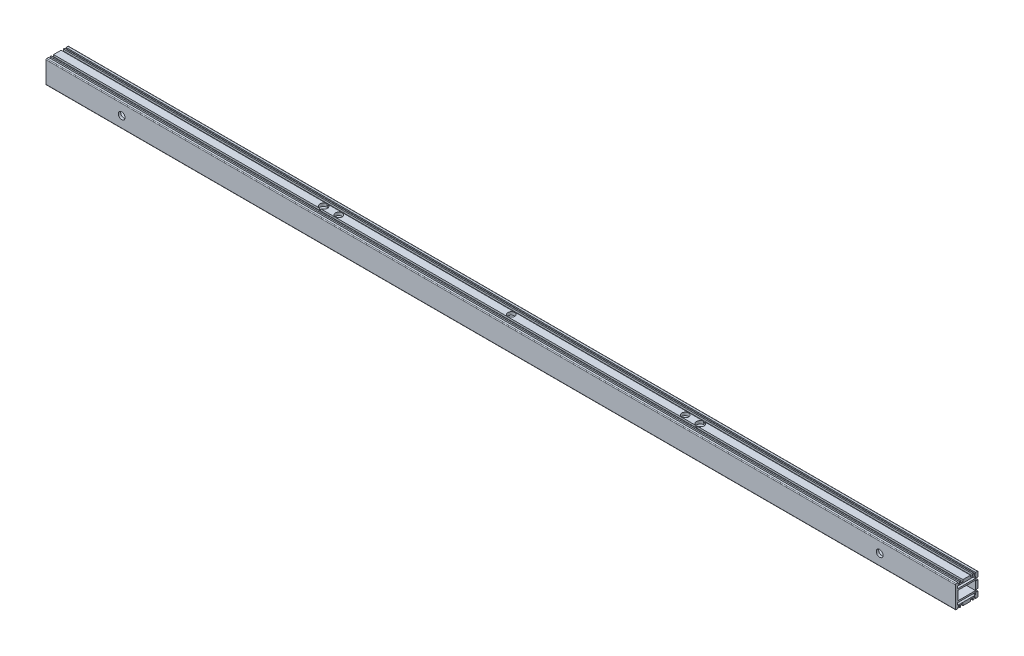
SolidWorks part; units mm, degrees
ref_plane "前视基准面" through (0, 0, 0) normal (0, 0, 1) x (1, 0, 0)
ref_plane "上视基准面" through (0, 0, 0) normal (0, 1, 0) x (1, 0, 0)
ref_plane "右视基准面" through (0, 0, 0) normal (1, 0, 0) x (0, 0, -1)
sketch "草图1" plane through (0, 0, 0) normal (1, 0, 0) x (0, 0, -1)
  line L0 (-15, 15) -> (15, -15) construction
  line L1 (-14, 15) -> (-11.5, 15)
  line L2 (-15, 14) -> (-15, -14)
  line L3 (-14, -15) -> (-11.5, -15)
  line L4 (15, 14) -> (15, 8)
  line L5 (15, 15) -> (-15, -15) construction
  line L6 (-11.5, 15) -> (-11.5, 13.5)
  line L7 (-11.5, 13.5) -> (-11.4, 13.5)
  line L8 (-11, 13.1) -> (-11, 12)
  line L9 (-11, 12) -> (-9.5, 12)
  line L10 (-9.5, 12) -> (-9.5, 15)
  line L11 (-9.5, 15) -> (-8, 15)
  line L12 (-8, 15) -> (-8, 12.5)
  line L13 (-8, 12.5) -> (-5, 12.5)
  line L14 (-5, 12.5) -> (-5, 15)
  line L15 (-5, 15) -> (5, 15)
  line L16 (0, 21.5201) -> (0, -18.309) construction
  line L17 (0, 55) -> (0, -55) construction
  line L18 (5, 12.5) -> (5, 15)
  line L19 (8, 12.5) -> (5, 12.5)
  line L20 (8, 15) -> (8, 12.5)
  line L21 (9.5, 15) -> (8, 15)
  line L22 (9.5, 12) -> (9.5, 15)
  line L23 (11, 12) -> (9.5, 12)
  line L24 (11, 13.1) -> (11, 12)
  line L25 (11.5, 13.5) -> (11.4, 13.5)
  line L26 (11.5, 15) -> (11.5, 13.5)
  line L27 (8, 15) -> (9.5, 15)
  line L28 (11.5, 15) -> (14, 15)
  line L29 (-19.8303, 0) -> (22.13, 0) construction
  line L30 (55, 0) -> (-55, 0) construction
  line L31 (8, -15) -> (9.5, -15)
  line L32 (11.5, -15) -> (11.5, -13.5)
  line L33 (11.5, -13.5) -> (11.4, -13.5)
  line L34 (11, -13.1) -> (11, -12)
  line L35 (11, -12) -> (9.5, -12)
  line L36 (9.5, -12) -> (9.5, -15)
  line L37 (9.5, -15) -> (8, -15)
  line L38 (8, -15) -> (8, -12.5)
  line L39 (8, -12.5) -> (5, -12.5)
  line L40 (5, -12.5) -> (5, -15)
  line L41 (-5, -15) -> (5, -15)
  line L42 (-5, -12.5) -> (-5, -15)
  line L43 (-8, -12.5) -> (-5, -12.5)
  line L44 (-8, -15) -> (-8, -12.5)
  line L45 (-9.5, -15) -> (-8, -15)
  line L46 (-9.5, -12) -> (-9.5, -15)
  line L47 (-11, -12) -> (-9.5, -12)
  line L48 (-11, -13.1) -> (-11, -12)
  line L49 (-11.5, -13.5) -> (-11.4, -13.5)
  line L50 (-11.5, -15) -> (-11.5, -13.5)
  line L51 (-9.5, -15) -> (-8, -15)
  line L52 (-5, -15) -> (5, -15)
  line L53 (8, -15) -> (9.5, -15)
  line L54 (11.5, -15) -> (14, -15)
  line L55 (15, 8) -> (12.5, 8)
  line L56 (12.5, 8) -> (12.5, 5)
  line L57 (12.5, 5) -> (15, 5)
  line L58 (12.5, -5) -> (15, -5)
  line L59 (12.5, -8) -> (12.5, -5)
  line L60 (15, -8) -> (12.5, -8)
  line L61 (15, 5) -> (15, -5)
  line L62 (15, -8) -> (15, -14)
  line L63 (12, -10.5) -> (12, -8.5)
  line L64 (-11.5, 11) -> (11.5, 11)
  line L65 (-12, 10.5) -> (-12, 8.5)
  line L66 (-11.5, 8) -> (11.5, 8)
  line L67 (12, 10.5) -> (12, 8.5)
  line L68 (-11.5, -8) -> (11.5, -8)
  line L69 (-12, -10.5) -> (-12, -8.5)
  line L70 (-11.5, -11) -> (11.5, -11)
  line L72 (-11.75, 6) -> (11.75, 6)
  line L73 (-11.75, 6) -> (-11.75, -6)
  line L74 (-11.75, -6) -> (11.75, -6)
  line L75 (11.75, 6) -> (11.75, -6)
  arc A0 (12, 8.5) -> (11.5, 8) centre (11.5, 8.5) cw
  arc A1 (11.5, 11) -> (12, 10.5) centre (11.5, 10.5) cw
  arc A2 (-11.5, 11) -> (-12, 10.5) centre (-11.5, 10.5) ccw
  arc A3 (-11.5, 8) -> (-12, 8.5) centre (-11.5, 8.5) cw
  arc A4 (-11, -13.1) -> (-11.4, -13.5) centre (-11.4, -13.1) cw
  arc A5 (11.4, -13.5) -> (11, -13.1) centre (11.4, -13.1) cw
  arc A6 (11.4, 13.5) -> (11, 13.1) centre (11.4, 13.1) ccw
  arc A7 (-11, 13.1) -> (-11.4, 13.5) centre (-11.4, 13.1) ccw
  arc A8 (-11.5, -8) -> (-12, -8.5) centre (-11.5, -8.5) ccw
  arc A9 (-11.5, -11) -> (-12, -10.5) centre (-11.5, -10.5) cw
  arc A10 (11.5, -11) -> (12, -10.5) centre (11.5, -10.5) ccw
  arc A11 (12, -8.5) -> (11.5, -8) centre (11.5, -8.5) ccw
  arc A12 (14, 15) -> (15, 14) centre (14, 14) cw
  arc A13 (14, -15) -> (15, -14) centre (14, -14) ccw
  arc A14 (-15, -14) -> (-14, -15) centre (-14, -14) ccw
  arc A15 (-15, 14) -> (-14, 15) centre (-14, 14) cw
  point P69 (12, 11)
  point P72 (-12, 11)
  point P77 (-11, -13.5)
  point P80 (11, -13.5)
  point P83 (11, 13.5)
  point P86 (-11, 13.5)
  point P99 (-12, -11)
  point P100 (12, -11)
  dimension "D17" = 0.5
  dimension "D18" = 0.4
  dimension "D21" = 1
  dimension "D1" = 3.5
  dimension "D2" = 1.5
  dimension "D3" = 0.5
  dimension "D4" = 1.5
  dimension "D5" = 3
  dimension "D6" = 30
  dimension "D7" = 30
  dimension "D8" = 1.5
  dimension "D9" = 2.5
  dimension "D10" = 3
  dimension "D11" = 2.5
  dimension "D12" = 7
  dimension "D13" = 3
  dimension "D14" = 4
  dimension "D15" = 3
  dimension "D16" = 24
  dimension "D19" = 23.5
  dimension "D20" = 12
extrude "凸台-拉伸1" add sketch "草图1" along normal mid plane 1202 contours A15 L2 A14 L3 L50 L49 A4 L48 L47 L46 L45 L44 L43 L42 L41 L40 L39 L38 L31 L36 L35 L34 A5 L33 L32 L54 A13 L62 L60 L59 L58 L61 L57 L56 L55 L4 A12 L28 L26 L25 A6 L24 L23 L22 L21 L20 L19 L18 L15 L14 L13
hole_wizard "M6 螺纹孔1" positions "草图6" profile "草图5" tap size "M6" standard "GB"
sketch "草图6" plane through (0, 0, -15) normal (0, 0, -1) x (-1, 0, 0)
  line L0 (-571, -5) -> (-571, 5) construction
  line L1 (-601, 15) -> (601, 15) construction
  point P0 (-551, 0)
  point P6 (-536, 0)
  point P9 (551, 0)
  point P12 (536, 0)
  dimension "D1" = 20
  dimension "D2" = 15
sketch "草图5" plane through (551, 0, -15) normal (1, 0, 0) x (0, 1, 0)
  line L0 (0, 0) -> (0, 16.5022)
  line L1 (0, 16.5022) -> (2.5, 15)
  line L2 (2.5, 15) -> (2.5, 0)
  line L5 (2.5, 0) -> (0, 0)
  line L10 (0, 16.5022) -> (-2.5, 15) construction
  line L11 (0, -6.35) -> (0, 107.95) construction
  dimension "螺纹孔钻头直径" = 5
  dimension "螺纹孔钻头深度" = 15
  dimension "导头角度" = 118
cosmetic thread "孔螺蚊线1" parameters "D1"=3.25, "D2"=6
cosmetic thread "孔螺蚊线2" parameters "D1"=3.25, "D2"=6
cosmetic thread "孔螺蚊线3" parameters "D1"=3.25, "D2"=6
cosmetic thread "孔螺蚊线4" parameters "D1"=3.25, "D2"=6
hole_wizard "M6 螺纹孔2" positions "草图8" profile "草图7" tap size "M6" standard "GB"
sketch "草图8" plane through (0, -15, 0) normal (0, -1, 0) x (1, 0, 0)
  line L2 (601, 15) -> (-601, 15) construction
  line L3 (601, 5) -> (601, -5) construction
  line L4 (-601, 5) -> (-601, -5) construction
  point P20 (-551, 0)
  point P22 (-536, 0)
  point P24 (536, 0)
  point P26 (551, 0)
  dimension "D1" = 15
  dimension "D2" = 15
  dimension "D3" = 50
  dimension "D4" = 50
  dimension "D5" = 15
sketch "草图7" plane through (-551, -15, 0) normal (1, 0, 0) x (0, 0, -1)
  line L0 (0, 0) -> (0, 16.5022)
  line L1 (0, 16.5022) -> (2.5, 15)
  line L2 (2.5, 15) -> (2.5, 0)
  line L5 (2.5, 0) -> (0, 0)
  line L10 (0, 16.5022) -> (-2.5, 15) construction
  line L11 (0, -6.35) -> (0, 107.95) construction
  dimension "螺纹孔钻头直径" = 5
  dimension "螺纹孔钻头深度" = 15
  dimension "导头角度" = 118
cosmetic thread "孔螺蚊线5" parameters "D1"=9, "D2"=6
cosmetic thread "孔螺蚊线6" parameters "D1"=9, "D2"=6
cosmetic thread "孔螺蚊线7" parameters "D1"=9, "D2"=6
cosmetic thread "孔螺蚊线8" parameters "D1"=9, "D2"=6
sketch "草图9" plane through (0, 0, 15) normal (0, 0, 1) x (1, 0, 0)
  line L0 (601, 0) -> (-601, 0) construction
  line L1 (601, 14) -> (601, -14) construction
  line L2 (-601, 14) -> (-601, -14) construction
  circle A0 centre (501, 0) radius 4.5
  circle A1 centre (-501, 0) radius 4.5
  dimension "D3" = 9
  dimension "D1" = 100
  dimension "D2" = 100
extrude "切除-拉伸1" cut sketch "草图9" against normal through all
sketch "草图12" plane through (0, -15, 0) normal (0, -1, 0) x (1, 0, 0)
  line L0 (601, 0) -> (-601, 0) construction
  line L1 (601, 5) -> (601, -5) construction
  line L2 (-601, 5) -> (-601, -5) construction
  circle A0 centre (-249, 0) radius 5.05
  circle A1 centre (249, 0) radius 5.05
  dimension "D3" = 10.1
  dimension "D1" = 352
  dimension "D2" = 352
extrude "切除-拉伸6" cut sketch "草图12" against normal through all
hole_wizard "M6 螺纹孔3" positions "草图14" profile "草图13" tap size "M6" standard "GB"
sketch "草图14" plane through (0, -15, 0) normal (0, -1, 0) x (1, 0, 0)
  line L0 (601, 15) -> (-601, 15) construction
  line L1 (-601, 5) -> (-601, -5) construction
  line L2 (601, 5) -> (601, -5) construction
  point P0 (-229, 0)
  point P1 (-1, 0)
  point P3 (229, 0)
  dimension "D1" = 15
  dimension "D2" = 372
  dimension "D3" = 372
  dimension "D4" = 15
  dimension "D5" = 15
  dimension "D6" = 602
sketch "草图13" plane through (-229, -15, 0) normal (1, 0, 0) x (0, 0, -1)
  line L0 (0, 0) -> (0, 16.5022)
  line L1 (0, 16.5022) -> (2.5, 15)
  line L2 (2.5, 15) -> (2.5, 0)
  line L5 (2.5, 0) -> (0, 0)
  line L10 (0, 16.5022) -> (-2.5, 15) construction
  line L11 (0, -6.35) -> (0, 107.95) construction
  dimension "螺纹孔钻头直径" = 5
  dimension "螺纹孔钻头深度" = 15
  dimension "导头角度" = 118
cosmetic thread "孔螺蚊线9" parameters "D1"=9, "D2"=6
cosmetic thread "孔螺蚊线10" parameters "D1"=9, "D2"=6
cosmetic thread "孔螺蚊线11" parameters "D1"=9, "D2"=6
sketch "草图15" plane through (0, 15, 0) normal (0, 1, 0) x (-1, 0, 0)
  circle A0 centre (229, 0) radius 4.5
  circle A1 centre (1, 0) radius 4.5
  circle A2 centre (-229, 0) radius 4.5
  dimension "D1" = 9
extrude "切除-拉伸7" cut sketch "草图15" against normal blind 15
hole_wizard "M6 螺纹孔4" positions "草图17" profile "草图16" tap size "M6" standard "GB"
sketch "草图17" plane through (0, 0, -15) normal (0, 0, -1) x (-1, 0, 0)
  line L1 (-601, 14) -> (-601, 8) construction
  line L2 (601, 5) -> (601, -5) construction
  line L3 (249.7089, 15) -> (601, 15) construction
  point P0 (341, 0)
  point P1 (281, 0)
  point P3 (-281, 0)
  point P5 (-341, 0)
  dimension "D1" = 60
  dimension "D2" = 260
  dimension "D3" = 260
  dimension "D4" = 60
  dimension "D5" = 15
sketch "草图16" plane through (-341, 0, -15) normal (1, 0, 0) x (0, 1, 0)
  line L0 (0, 0) -> (0, 16.5022)
  line L1 (0, 16.5022) -> (2.5, 15)
  line L2 (2.5, 15) -> (2.5, 0)
  line L5 (2.5, 0) -> (0, 0)
  line L10 (0, 16.5022) -> (-2.5, 15) construction
  line L11 (0, -6.35) -> (0, 107.95) construction
  dimension "螺纹孔钻头直径" = 5
  dimension "螺纹孔钻头深度" = 15
  dimension "导头角度" = 118
cosmetic thread "孔螺蚊线12" parameters "D1"=3.25, "D2"=6
cosmetic thread "孔螺蚊线13" parameters "D1"=3.25, "D2"=6
cosmetic thread "孔螺蚊线14" parameters "D1"=3.25, "D2"=6
cosmetic thread "孔螺蚊线15" parameters "D1"=3.25, "D2"=6
hole_wizard "M6 螺纹孔5" positions "草图19" profile "草图18" tap size "M6" standard "GB"
sketch "草图19" plane through (0, 0, -15) normal (0, 0, -1) x (-1, 0, 0)
  line L0 (249.7089, 15) -> (601, 15) construction
  line L1 (601, 5) -> (601, -5) construction
  point P0 (446, 0)
  point P1 (376, 0)
  dimension "D1" = 15
  dimension "D2" = 15
  dimension "D3" = 70
  dimension "D4" = 155
sketch "草图18" plane through (-446, 0, -15) normal (1, 0, 0) x (0, 1, 0)
  line L0 (0, 0) -> (0, 16.5022)
  line L1 (0, 16.5022) -> (2.5, 15)
  line L2 (2.5, 15) -> (2.5, 0)
  line L5 (2.5, 0) -> (0, 0)
  line L10 (0, 16.5022) -> (-2.5, 15) construction
  line L11 (0, -6.35) -> (0, 107.95) construction
  dimension "螺纹孔钻头直径" = 5
  dimension "螺纹孔钻头深度" = 15
  dimension "导头角度" = 118
cosmetic thread "孔螺蚊线16" parameters "D1"=3.25, "D2"=6
cosmetic thread "孔螺蚊线17" parameters "D1"=3.25, "D2"=6
